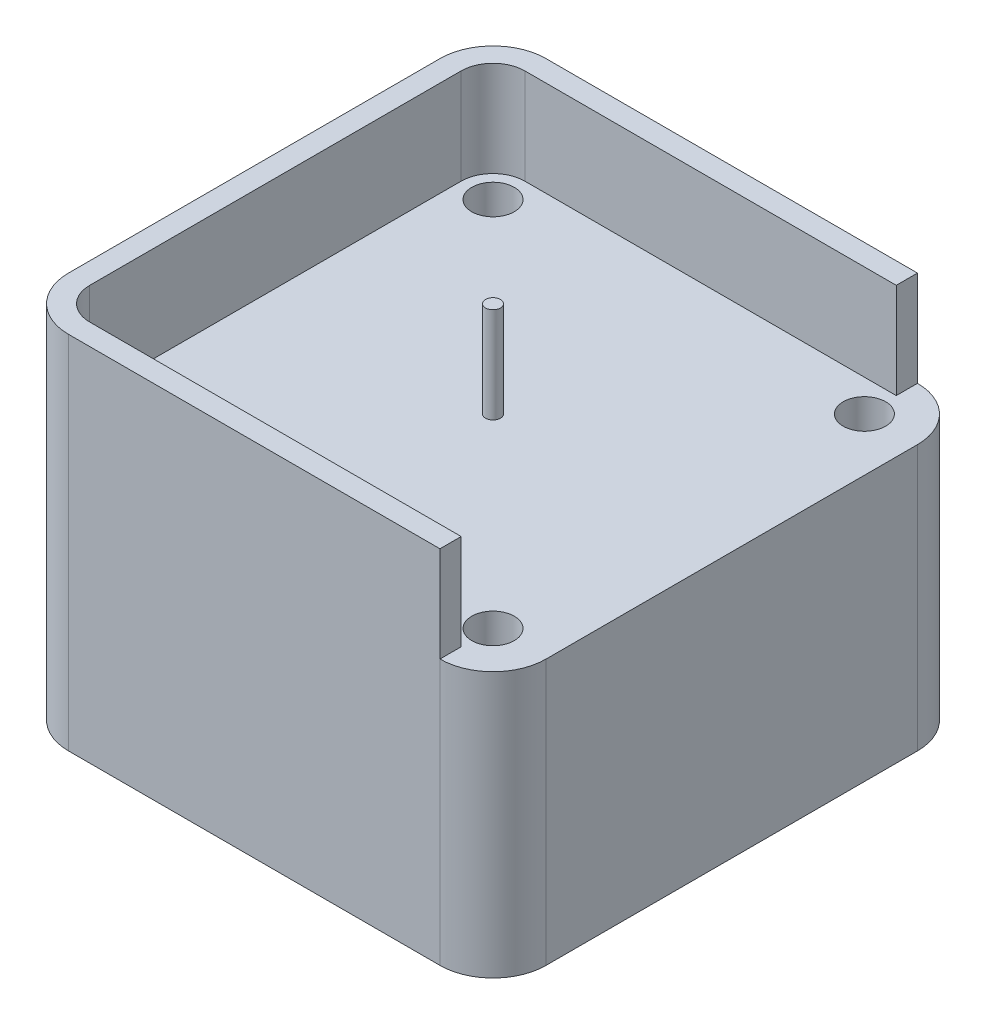
SolidWorks part; units mm, degrees
ref_plane "Front Plane" through (0, 0, 0) normal (0, 0, 1) x (1, 0, 0)
ref_plane "Top Plane" through (0, 0, 0) normal (0, 1, 0) x (1, 0, 0)
ref_plane "Right Plane" through (0, 0, 0) normal (1, 0, 0) x (0, 0, -1)
sketch "Sketch1" plane through (0, 0, 0) normal (0, 1, 0) x (1, 0, 0)
  line L1 (-53.8898, 53.2415) -> (16.1102, 53.2415)
  line L2 (-63.8898, 43.2415) -> (-63.8898, -26.7585)
  line L3 (-53.8898, -36.7585) -> (16.1102, -36.7585)
  line L4 (26.1102, 43.2415) -> (26.1102, -26.7585)
  arc A0 (16.1102, 53.2415) -> (26.1102, 43.2415) centre (16.1102, 43.2415) cw
  arc A1 (16.1102, -36.7585) -> (26.1102, -26.7585) centre (16.1102, -26.7585) ccw
  arc A2 (-63.8898, -26.7585) -> (-53.8898, -36.7585) centre (-53.8898, -26.7585) ccw
  arc A3 (-53.8898, 53.2415) -> (-63.8898, 43.2415) centre (-53.8898, 43.2415) ccw
  circle A4 centre (-53.8898, 43.2415) radius 4
  circle A5 centre (16.1102, 43.2415) radius 4
  circle A6 centre (16.1102, -26.7585) radius 4
  circle A7 centre (-53.8898, -26.7585) radius 4
  point P7 (26.1102, 53.2415)
  point P10 (26.1102, -36.7585)
  point P15 (-63.8898, 53.2415)
  dimension "D3" = 10
  dimension "D4" = 8
  dimension "D1" = 90
  dimension "D2" = 90
  dimension "D5" = 2
  dimension "D6" = 2
extrude "Boss-Extrude1" add sketch "Sketch1" along normal blind 50
sketch "Sketch2" plane through (0, 50, 0) normal (0, 1, 0) x (1, 0, 0)
  line L8 (16.1102, 49.2415) -> (-53.8898, 49.2415)
  line L9 (-59.8898, 43.2415) -> (-59.8898, -26.7585)
  line L10 (-53.8898, -32.7585) -> (16.1102, -32.7585)
  line L11 (22.1102, -26.7585) -> (22.1102, 43.2415)
  line L12 (16.1102, 49.2415) -> (-53.8898, 49.2415)
  line L13 (-59.8898, 43.2415) -> (-59.8898, -26.7585)
  line L14 (-53.8898, -32.7585) -> (16.1102, -32.7585)
  line L15 (22.1102, -26.7585) -> (22.1102, 43.2415)
  arc A8 (22.1102, 43.2415) -> (16.1102, 49.2415) centre (16.1102, 43.2415) ccw
  arc A9 (-53.8898, 49.2415) -> (-59.8898, 43.2415) centre (-53.8898, 43.2415) ccw
  arc A10 (-59.8898, -26.7585) -> (-53.8898, -32.7585) centre (-53.8898, -26.7585) ccw
  arc A11 (16.1102, -32.7585) -> (22.1102, -26.7585) centre (16.1102, -26.7585) ccw
  arc A12 (22.1102, 43.2415) -> (16.1102, 49.2415) centre (16.1102, 43.2415) ccw
  arc A13 (-53.8898, 49.2415) -> (-59.8898, 43.2415) centre (-53.8898, 43.2415) ccw
  arc A14 (-59.8898, -26.7585) -> (-53.8898, -32.7585) centre (-53.8898, -26.7585) ccw
  arc A15 (16.1102, -32.7585) -> (22.1102, -26.7585) centre (16.1102, -26.7585) ccw
  dimension "D1" = 4
extrude "Extrude-Thin1" add sketch "Sketch2" along normal blind 18 thin
sketch "Sketch3" plane through (0, 50, 0) normal (0, 1, 0) x (1, 0, 0)
  line L0 (16.1102, 49.2415) -> (-53.8898, 49.2415) construction
  line L1 (-59.8898, 43.2415) -> (-59.8898, -26.7585) construction
  circle A0 centre (-18.8898, 8.2415) radius 1.4
  dimension "D1" = 41
  dimension "D2" = 41
extrude "Boss-Extrude2" add sketch "Sketch3" along normal blind 18
sketch "Sketch4" plane through (0, 68, 0) normal (0, 1, 0) x (1, 0, 0)
  line L0 (22.1102, 43.2415) -> (22.1102, -26.7585)
  line L1 (22.1102, 43.2415) -> (26.5222, 43.2415)
  line L2 (22.1102, -26.7585) -> (26.5222, -26.7585)
  line L3 (26.5222, 43.2415) -> (26.5222, -26.7585)
extrude "Cut-Extrude1" cut sketch "Sketch4" against normal blind 18
sketch "Sketch5" plane through (0, 68, 0) normal (0, 1, 0) x (1, 0, 0)
  line L0 (16.1102, 53.2415) -> (28.1904, 53.2415)
  line L1 (16.1102, 53.2415) -> (16.1102, 39.3187)
  line L2 (28.1904, 53.2415) -> (28.1904, 39.3187)
  line L3 (16.1102, 39.3187) -> (28.1904, 39.3187)
  line L4 (16.1102, -36.7585) -> (16.1102, -18.9296)
  line L5 (16.1102, -36.7585) -> (30.8114, -36.7585)
  line L6 (16.1102, -18.9296) -> (30.8114, -18.9296)
  line L7 (30.8114, -36.7585) -> (30.8114, -18.9296)
extrude "Cut-Extrude2" cut sketch "Sketch5" against normal blind 18
